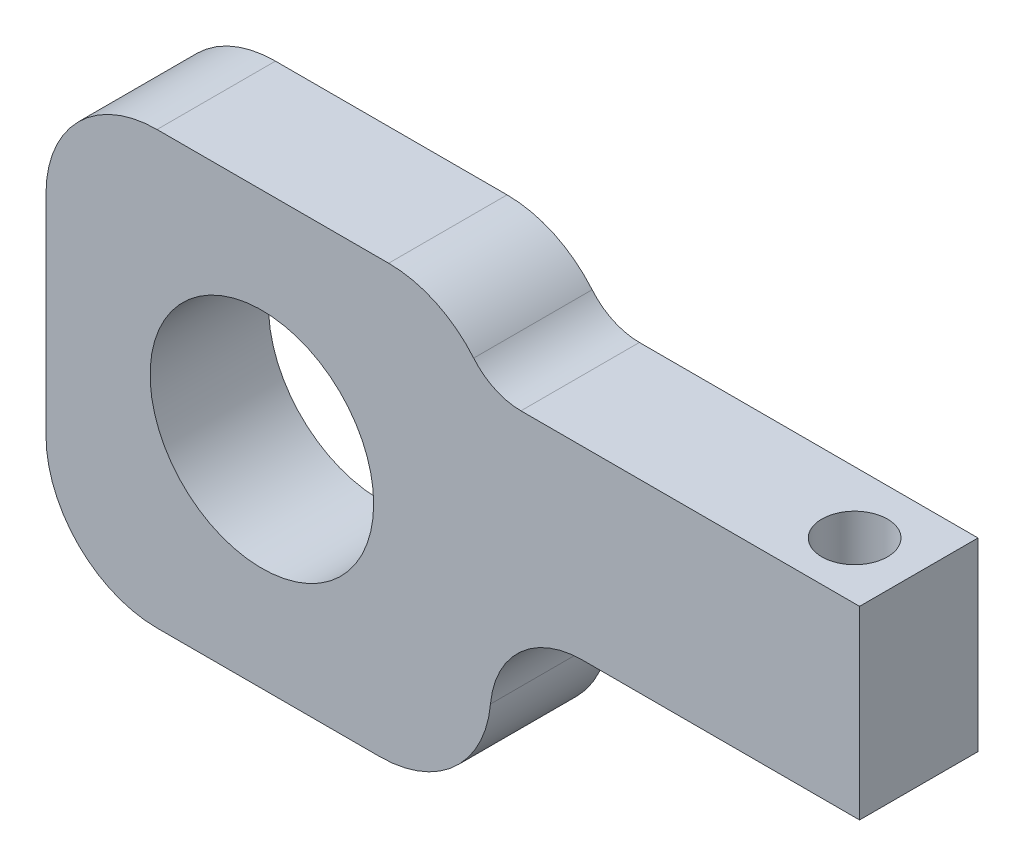
SolidWorks part; units mm, degrees
other "Clamp"
material "6061 Alloy"
ref_plane "Front Plane" through (0, 0, 0) normal (0, 0, 1) x (1, 0, 0)
ref_plane "Top Plane" through (0, 0, 0) normal (0, 1, 0) x (1, 0, 0)
ref_plane "Right Plane" through (0, 0, 0) normal (1, 0, 0) x (0, 0, -1)
sketch "Sketch1" plane through (0, 0, 0) normal (0, 0, 1) x (1, 0, 0)
  line L1 (0, 0) -> (96.52, 0)
  line L2 (0, 0) -> (0, -44.45)
  line L3 (0, -44.45) -> (96.52, -44.45)
  line L4 (96.52, 0) -> (96.52, -44.45)
  dimension "D1" = 44.45
  dimension "D2" = 96.52
extrude "Boss-Extrude1" add sketch "Sketch1" along normal mid plane 12.192
sketch "Sketch2" plane through (0, 0, 6.096) normal (0, 0, 1) x (1, 0, 0)
  circle A0 centre (22.225, -22.225) radius 11.5087
  dimension "D1" = 23.0175
  dimension "D2" = 22.225
  dimension "D3" = 22.225
extrude "Cut-Extrude1" cut sketch "Sketch2" against normal up to next
sketch "Sketch3" plane through (0, 0, 0) normal (0, 1, 0) x (1, 0, 0)
  line L1 (96.52, 6.096) -> (0, 6.096) construction
  line L2 (96.52, -6.096) -> (96.52, 6.096) construction
  circle A0 centre (77.4065, -0.254) radius 3.3782
  dimension "D1" = 6.7564
  dimension "D2" = 19.1135
  dimension "D3" = 6.35
extrude "Cut-Extrude2" cut sketch "Sketch3" against normal up to next
sketch "Sketch4" plane through (0, 0, 6.096) normal (0, 0, 1) x (1, 0, 0)
  line L0 (48.895, 0) -> (96.52, 0) construction
  line L1 (96.52, 0) -> (0, 0) construction
  line L2 (48.895, 6.35) -> (96.52, 6.35)
  line L3 (48.895, -6.35) -> (96.52, -6.35)
  line L4 (96.52, -34.925) -> (55.245, -34.925) construction
  line L5 (45.72, -34.925) -> (45.72, -44.45)
  line L8 (96.52, -44.45) -> (96.52, 0) construction
  line L9 (96.52, -44.45) -> (55.245, -44.45)
  line L10 (96.52, -25.4) -> (55.245, -25.4)
  line L11 (0, -44.45) -> (96.52, -44.45) construction
  line L12 (45.72, -44.45) -> (55.245, -44.45)
  arc A0 (48.895, 6.35) -> (48.895, -6.35) centre (48.895, 0) ccw
  arc A1 (96.52, -6.35) -> (96.52, 6.35) centre (96.52, 0) ccw
  arc A4 (96.52, -44.45) -> (96.52, -25.4) centre (96.52, -34.925) ccw
  arc A5 (55.245, -25.4) -> (45.72, -34.925) centre (55.245, -34.925) ccw
  point P5 (72.7075, 0)
  dimension "D1" = 6.35
  dimension "D3" = 9.525
  dimension "D2" = 47.625
  dimension "D4" = 41.275
extrude "Cut-Extrude3" cut sketch "Sketch4" against normal up to next
sketch "Sketch7" plane through (0, -6.35, 0) normal (0, 1, 0) x (1, 0, 0)
  line L0 (96.52, 6.096) -> (48.895, 6.096) construction
  line L1 (96.52, -6.096) -> (83.7565, -6.096)
  line L2 (96.52, -6.096) -> (96.52, 6.096)
  line L3 (96.52, 6.096) -> (83.7565, 6.096)
  line L4 (83.7565, -6.096) -> (83.7565, 6.096)
  dimension "D1" = 12.7635
extrude "Cut-Extrude5" cut sketch "Sketch7" against normal through all
fillet "Fillet1" radius 11.43 4 edges at (42.545, 0, 0) (45.72, -44.45, 0) (0, -44.45, 0) (0, 0, 0)
sketch "Sketch5" plane through (0, 0, 6.096) normal (0, 0, 1) x (1, 0, 0)
  line L0 (2.54, -2.54) -> (2.54, -63.661) construction
  line L1 (2.54, -2.54) -> (64.1242, -2.54) construction
  line L6 (3.9148, -3.6512) -> (3.3649, -2.6987)
  line L8 (3.0899, -2.54) -> (1.9901, -2.54)
  line L9 (1.7151, -2.6987) -> (1.1652, -3.6512)
  line L10 (1.1652, -3.9688) -> (1.7151, -4.9212)
  line L11 (1.9901, -5.08) -> (3.0899, -5.08)
  line L12 (3.3649, -4.9212) -> (3.9148, -3.9688)
  line L47 (71.0565, -12.3444) -> (71.0565, -19.4056) construction
  line L48 (83.7565, -25.4) -> (83.7565, -6.35) construction
  line L53 (81.2165, -22.86) -> (81.2165, -8.89)
  line L54 (55.245, -22.86) -> (81.2165, -22.86)
  line L55 (11.43, -41.91) -> (34.3768, -41.91)
  line L56 (2.54, -11.43) -> (2.54, -33.02)
  line L57 (35.2758, -2.54) -> (11.43, -2.54)
  line L58 (81.2165, -8.89) -> (48.895, -8.89)
  line L60 (55.245, -22.86) -> (67.6021, -22.86) construction
  line L61 (11.43, -41.91) -> (34.3768, -41.91) construction
  line L62 (2.54, -11.43) -> (2.54, -33.02) construction
  line L63 (35.2758, -2.54) -> (11.43, -2.54) construction
  line L64 (67.6021, -8.89) -> (48.895, -8.89) construction
  circle A0 centre (2.54, -3.81) radius 1.27 construction
  arc A5 (1.1652, -3.6512) -> (1.1652, -3.9688) centre (1.4401, -3.81) ccw
  arc A6 (1.7151, -4.9212) -> (1.9901, -5.08) centre (1.9901, -4.7625) ccw
  arc A8 (3.0899, -5.08) -> (3.3649, -4.9212) centre (3.0899, -4.7625) ccw
  arc A11 (3.9148, -3.9688) -> (3.9148, -3.6512) centre (3.6399, -3.81) ccw
  arc A12 (3.3649, -2.6987) -> (3.0899, -2.54) centre (3.0899, -2.8575) ccw
  arc A13 (1.9901, -2.54) -> (1.7151, -2.6987) centre (1.9901, -2.8575) ccw
  arc A53 (67.6021, -22.86) -> (71.0565, -19.4056) centre (67.6021, -19.4056) ccw construction
  circle A54 centre (22.225, -22.225) radius 14.0487
  circle A55 centre (22.225, -22.225) radius 14.0487 construction
  arc A56 (71.0565, -12.3444) -> (67.6021, -8.89) centre (67.6021, -12.3444) ccw construction
  arc A58 (55.245, -22.86) -> (43.23, -33.8282) centre (55.245, -34.925) ccw
  arc A59 (34.3768, -41.91) -> (43.23, -33.8282) centre (34.3768, -33.02) ccw
  arc A60 (2.54, -33.02) -> (11.43, -41.91) centre (11.43, -33.02) ccw
  arc A61 (11.43, -2.54) -> (2.54, -11.43) centre (11.43, -11.43) ccw
  arc A62 (42.0854, -5.715) -> (48.895, -8.89) centre (48.895, 0) ccw
  arc A63 (42.0854, -5.715) -> (35.2758, -2.54) centre (35.2758, -11.43) ccw
  arc A64 (55.245, -22.86) -> (43.23, -33.8282) centre (55.245, -34.925) ccw construction
  arc A65 (34.3768, -41.91) -> (43.23, -33.8282) centre (34.3768, -33.02) ccw construction
  arc A66 (2.54, -33.02) -> (11.43, -41.91) centre (11.43, -33.02) ccw construction
  arc A67 (11.43, -2.54) -> (2.54, -11.43) centre (11.43, -11.43) ccw construction
  arc A68 (42.0854, -5.715) -> (48.895, -8.89) centre (48.895, 0) ccw construction
  arc A69 (42.0854, -5.715) -> (35.2758, -2.54) centre (35.2758, -11.43) ccw construction
  point P15 (0, 0)
  dimension "D4" = 3.4544
  dimension "D6" = 0.3175
  dimension "D3" = 12.7
  dimension "D5" = 2.54
  dimension "D1" = 2.54
  dimension "D2" = 2.54
